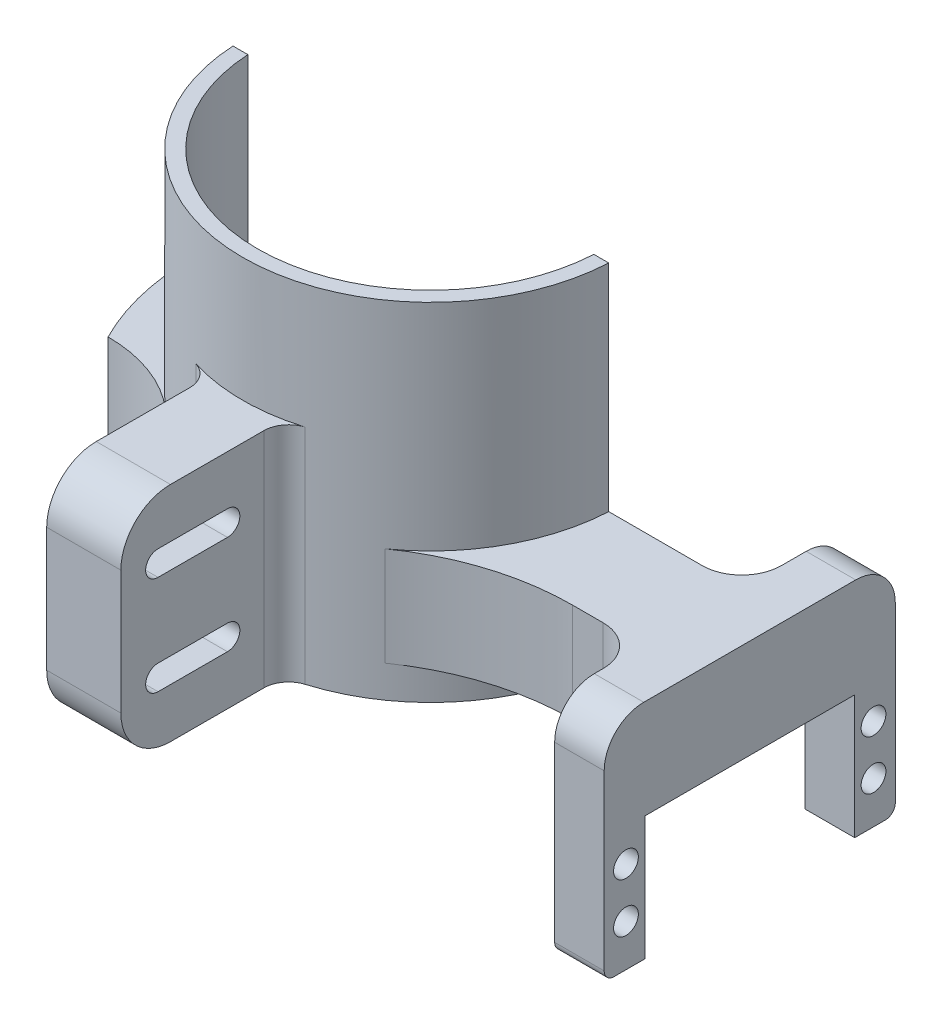
SolidWorks part; units mm, degrees
ref_plane "Plan de face" through (0, 0, 0) normal (0, 0, 1) x (1, 0, 0)
ref_plane "Plan de dessus" through (0, 0, 0) normal (0, 1, 0) x (1, 0, 0)
ref_plane "Plan de droite" through (0, 0, 0) normal (1, 0, 0) x (0, 0, -1)
sketch "Esquisse1" plane through (0, 11.1, 0) normal (0, -1, 0) x (0, 0, 1)
  line L0 (21.5809, -0.1736) -> (18.5809, -0.1736) construction
  line L2 (12.3809, -90) -> (-24.4191, -90) construction
  line L3 (18.5809, -0.1736) -> (-16.4191, -0.1736) construction
  line L4 (-16.4191, -0.1736) -> (-16.4191, 51.3784) construction
  line L5 (-14.4191, 37.7738) -> (-14.4191, 34.7692)
  line L6 (-14.4191, -38.1209) -> (-14.4191, -35.1164)
  arc A0 (-14.4191, -35.1164) -> (-14.4191, 34.7692) centre (-16.4191, -0.1736) ccw
  arc A1 (-14.4191, -38.1209) -> (-14.4191, 37.7738) centre (-16.4191, -0.1736) ccw
  circle A2 centre (-16.4191, -0.1736) radius 17.5 construction
  dimension "D1" = 70
  dimension "D2" = 3
  dimension "D3" = 2
extrude "Boss.-Extru.1" add sketch "Esquisse1" along normal blind 70
sketch "Esquisse2" plane through (0, -58.9, 0) normal (0, -1, 0) x (1, 0, 0)
  line L0 (0.1736, -16.4191) -> (0, 133.5809) construction
  line L1 (0, 0) -> (0, 85.5357) construction
  line L2 (-7.3695, 20.8248) -> (-7.4074, 53.5722)
  line L3 (-7.4074, 53.5722) -> (7.5926, 53.5896)
  line L4 (7.5926, 53.5896) -> (7.6305, 20.8421)
  arc A2 (38.1209, -14.4191) -> (-37.7738, -14.4191) centre (0.1736, -16.4191) ccw construction
  arc A4 (7.6305, 20.8421) -> (-7.3695, 20.8248) centre (0.1736, -16.4191) ccw
  dimension "D1" = 150
  dimension "D2" = 15
  dimension "D3" = 32
extrude "Boss.-Extru.2" add sketch "Esquisse2" against normal blind 45
ref_plane "plan sup servo" through (0, -52.4, 0) normal (0, 1, 0) x (1, 0, 0)
sketch "Esquisse3" plane through (-7.3454, 0, -0.0085) normal (-1, 0, -0.0012) x (-0.0012, 0, 1)
  line L0 (46.0808, -26.4) -> (32.0808, -26.4) construction
  line L1 (46.0808, -28.9) -> (32.0808, -28.9)
  line L2 (46.0808, -23.9) -> (32.0808, -23.9)
  line L3 (53.5808, -13.9) -> (53.5808, -58.9) construction
  line L4 (53.5808, -13.9) -> (20.8333, -13.9) construction
  line L5 (32.0808, -46.4) -> (46.0808, -46.4) construction
  line L6 (32.0808, -43.9) -> (46.0808, -43.9)
  line L7 (32.0808, -48.9) -> (46.0808, -48.9)
  line L8 (46.0808, -26.4) -> (46.0808, -46.4) construction
  arc A0 (46.0808, -28.9) -> (46.0808, -23.9) centre (46.0808, -26.4) ccw
  arc A1 (32.0808, -23.9) -> (32.0808, -28.9) centre (32.0808, -26.4) ccw
  arc A2 (32.0808, -43.9) -> (32.0808, -48.9) centre (32.0808, -46.4) ccw
  arc A3 (46.0808, -48.9) -> (46.0808, -43.9) centre (46.0808, -46.4) ccw
  point P2 (39.0808, -26.4)
  point P13 (39.0808, -46.4)
  dimension "D1" = 2.5
  dimension "D2" = 14
  dimension "D3" = 5
  dimension "D4" = 10
  dimension "D5" = 20
extrude "Enlèv. mat.-Extru.1" cut sketch "Esquisse3" against normal up to surface (15 mm away) up to face at (7.6115, -36.4, 37.2158)
sketch "Esquisse5" plane through (0, -52.4, 0) normal (0, -1, 0) x (1, 0, 0)
  line L0 (38.1209, -14.4191) -> (65, -14.4191)
  line L2 (65, -14.4191) -> (65, -35.4191)
  line L3 (65, -35.4191) -> (75, -35.4191)
  line L4 (75, -35.4191) -> (75, 23.3809)
  line L5 (75, 23.3809) -> (65, 23.3809)
  line L7 (65, 23.3809) -> (65, 5.5809)
  line L8 (65, -33.4191) -> (63, -33.4191) construction
  line L9 (65, -26.4191) -> (65, -31.4191) construction
  line L10 (63, 21.3809) -> (65, 21.3809) construction
  line L11 (65, 5.5809) -> (31.1574, 5.5809)
  line L12 (65, 19.3809) -> (65, 14.3809) construction
  arc A1 (38.1209, -14.4191) -> (7.6305, 20.8421) centre (0.1736, -16.4191) ccw construction
  arc A2 (38.1209, -14.4191) -> (31.1574, 5.5809) centre (0.1736, -16.4191) ccw
  dimension "D1" = 2
  dimension "D2" = 10
  dimension "D3" = 2
  dimension "D4" = 20
extrude "Boss.-Extru.6" add sketch "Esquisse5" against normal blind 20
sketch "Esquisse10" plane through (75, 0, 0) normal (1, 0, 0) x (0, 0, -1)
  line L0 (-14.3809, -73.9) -> (-14.3809, -53.9) construction
  line L1 (-23.3809, -52.4) -> (-15.1809, -52.4)
  line L2 (-23.3809, -52.4) -> (-23.3809, -77.4)
  line L3 (-23.3809, -77.4) -> (-15.1809, -77.4)
  line L4 (-15.1809, -52.4) -> (-15.1809, -77.4)
  line L5 (35.4191, -52.4) -> (-23.3809, -52.4) construction
  line L6 (27.2191, -52.4) -> (35.4191, -52.4)
  line L7 (27.2191, -52.4) -> (27.2191, -77.4)
  line L8 (27.2191, -77.4) -> (35.4191, -77.4)
  line L9 (35.4191, -52.4) -> (35.4191, -77.4)
  line L10 (26.4191, -53.9) -> (26.4191, -73.9) construction
  line L11 (35.4191, -32.4) -> (35.4191, -52.4) construction
  circle A0 centre (-18.9809, -58.9) radius 2.5
  circle A1 centre (-18.9809, -68.9) radius 2.5
  circle A3 centre (31.0191, -58.9) radius 2.5
  circle A4 centre (31.0191, -68.9) radius 2.5
  dimension "D3" = 5
  dimension "D1" = 25
  dimension "D2" = 0.8
  dimension "D4" = 0.8
extrude "Boss.-Extru.7" add sketch "Esquisse10" against normal up to surface (10 mm away) up to face at (65, -42.4, 14.4809)
sketch "Esquisse11" plane through (0, -63.9, 0) normal (0, -1, 0) x (0, 0, 1)
  line L0 (-16.4191, -90) -> (-16.4191, 110) construction
  line L1 (-16.4191, -47.2) -> (-16.4191, -51.2) construction
  line L2 (12.3809, -90) -> (-24.4191, -90) construction
  line L3 (-14.4191, 37.7738) -> (-14.4191, 42.7738)
  line L4 (-14.4191, 42.7738) -> (-23.4191, 42.7738)
  line L5 (-23.4191, 42.7738) -> (-23.4191, 47.7738)
  line L6 (-14.4191, 37.7738) -> (-14.4191, 34.7692)
  line L7 (5.5809, 42.9999) -> (5.5809, 30.8103) construction
  line L8 (-16.4191, -0.1736) -> (33.8293, 42.9999) construction
  line L9 (10.1279, 22.6356) -> (12.4034, 24.5907)
  arc A0 (20.8248, 7.3695) -> (-14.4191, 37.7738) centre (-16.4191, -0.1736) ccw construction
  arc A1 (5.5809, 30.8103) -> (-14.4191, 37.7738) centre (-16.4191, -0.1736) ccw construction
  arc A2 (5.5809, 42.9999) -> (-23.4191, 47.7738) centre (-16.4191, -0.1736) ccw
  arc A3 (-14.4191, -35.1164) -> (-14.4191, 34.7692) centre (-16.4191, -0.1736) ccw construction
  arc A4 (10.1279, 22.6356) -> (-14.4191, 34.7692) centre (-16.4191, -0.1736) ccw
  arc A5 (5.5809, 42.9999) -> (12.4034, 24.5907) centre (33.8293, 42.9999) ccw
  dimension "D1" = 200
  dimension "D2" = 5
  dimension "D3" = 9
  dimension "D4" = 20
  dimension "D5" = 5
extrude "Boss.-Extru.8" add sketch "Esquisse11" along normal blind 8 and the other way up to surface other way up to face at (60.0875, -32.4, -5.1572)
sketch "Esquisse12" plane through (0, 0, 0) normal (1, 0, 0) x (0, 0, -1)
  circle A0 centre (16.4191, -63.9) radius 10
  dimension "D1" = 20
extrude "Enlèv. mat.-Extru.2" cut sketch "Esquisse12" against normal up to surface (42.7738 mm away) up to face at (-42.7738, -52.15, -18.9191)
sketch "Esquisse13" plane through (0, 0, 0) normal (1, 0, 0) x (0, 0, -1)
  line L0 (14.4191, -32.4) -> (23.4191, -32.4) construction
  line L1 (14.4191, -32.4) -> (23.4191, -32.4)
  line L2 (23.4191, -32.4) -> (23.4191, -56.7586)
  line L3 (23.4191, -56.7586) -> (14.4191, -32.4)
  circle A0 centre (16.4191, -63.9) radius 2.25
  circle A2 centre (16.4191, -63.9) radius 10 construction
  arc A3 (14.4191, -54.102) -> (10.4191, -71.9) centre (16.4191, -63.9) ccw construction
  dimension "D1" = 4.5
extrude "Enlèv. mat.-Extru.3" cut sketch "Esquisse13" against normal blind 65
fillet "Congé5" radius 5 1 edges at (-45.2738, -71.9, -23.4191)
fillet "Congé6" radius 50 1 edges at (31.1574, -42.4, 5.5809)
fillet "Congé7" radius 5 2 edges at (-7.3695, -36.4, 20.8248) (7.6305, -36.4, 20.8421)
fillet "Congé8" radius 8 2 edges at (65, -42.4, -14.4191) (65, -42.4, 5.5809)
fillet "Congé9" radius 8 2 edges at (70, -32.4, -35.4191) (70, -32.4, 23.3809)
fillet "Congé10" radius 2 2 edges at (70, -77.4, 23.3809) (70, -77.4, -35.4191)
fillet "Congé11" radius 10 2 edges at (0.0926, -13.9, 53.5809) (0.0926, -58.9, 53.5809)
